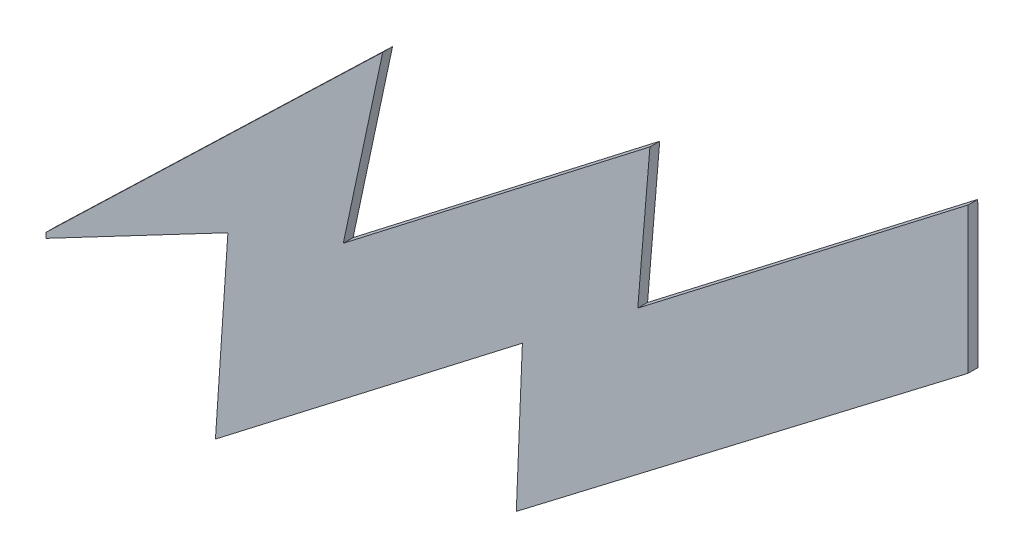
SolidWorks part; units mm, degrees
ref_plane "Front Plane" through (0, 0, 0) normal (0, 0, 1) x (1, 0, 0)
ref_plane "Top Plane" through (0, 0, 0) normal (0, 1, 0) x (1, 0, 0)
ref_plane "Right Plane" through (0, 0, 0) normal (1, 0, 0) x (0, 0, -1)
sketch "Model" plane through (0, 0, 0) normal (0, 0, 1) x (1, 0, 0)
  line L0 (46.9862, 22.1658) -> (23.9632, 4.5578)
  line L1 (23.9632, 4.5578) -> (24.2725, 12.137)
  line L2 (24.2725, 12.137) -> (8.6328, 0.0841)
  line L3 (8.6328, 0.0841) -> (9.2687, 9.5079)
  line L4 (9.2687, 9.5079) -> (0, 4.6262)
  line L5 (0, 4.6262) -> (0.0119, 4.9034)
  line L6 (0.0119, 4.9034) -> (17.1571, 21.4182)
  line L7 (17.1571, 21.4182) -> (15.1465, 11.9824)
  line L8 (15.1465, 11.9824) -> (30.7693, 24.0474)
  line L9 (30.7693, 24.0474) -> (30.1503, 16.6228)
  line L10 (30.1503, 16.6228) -> (46.9732, 29.5833)
  line L11 (46.9732, 29.5833) -> (46.9862, 22.1658)
extrude "Boss-Extrude1" add sketch "Model" along normal blind 0.5
